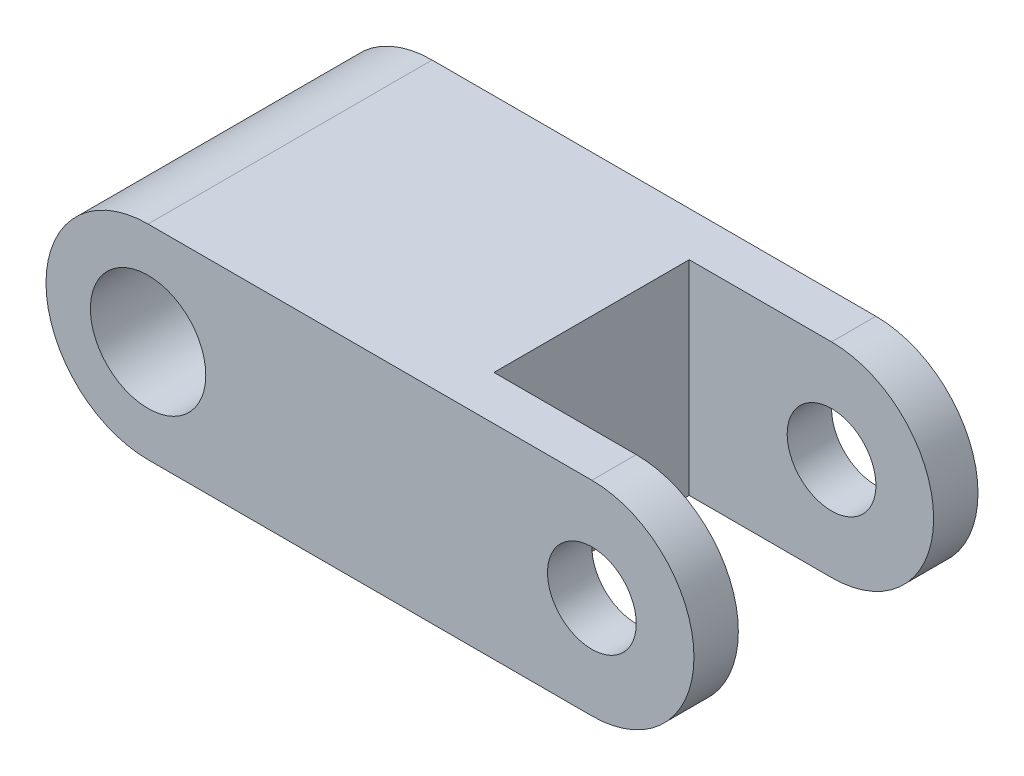
SolidWorks part; units mm, degrees
ref_plane "Front Plane" through (0, 0, 0) normal (0, 0, 1) x (1, 0, 0)
ref_plane "Top Plane" through (0, 0, 0) normal (0, 1, 0) x (1, 0, 0)
ref_plane "Right Plane" through (0, 0, 0) normal (1, 0, 0) x (0, 0, -1)
sketch "Sketch1" plane through (0, 0, 0) normal (0, 0, 1) x (1, 0, 0)
  line L0 (0, 0) -> (50, 0) construction
  line L1 (0, 11.5) -> (50, 11.5)
  line L2 (0, -11.5) -> (50, -11.5)
  arc A0 (0, 11.5) -> (0, -11.5) centre (0, 0) ccw
  arc A1 (50, -11.5) -> (50, 11.5) centre (50, 0) ccw
  circle A2 centre (0, 0) radius 6.5
  circle A3 centre (50, 0) radius 5
  point P3 (25, 0)
  dimension "D1" = 5
  dimension "D3" = 10
  dimension "D4" = 13
  dimension "D2" = 50
extrude "Boss-Extrude1" add sketch "Sketch1" along normal blind 32
sketch "Sketch2" plane through (0, 11.5, 0) normal (0, 1, 0) x (1, 0, 0)
  line L0 (61.5, -32) -> (61.5, 0) construction
  line L1 (61.5, -5) -> (33.9665, -5)
  line L2 (61.5, -5) -> (61.5, -27)
  line L3 (61.5, -27) -> (33.9665, -27)
  line L4 (33.9665, -5) -> (33.9665, -27)
  line L5 (50, -32) -> (50, 0) construction
  point P8 (50, -16)
  point P9 (33.9665, -16)
  dimension "D1" = 22
extrude "Cut-Extrude1" cut sketch "Sketch2" against normal up to next
